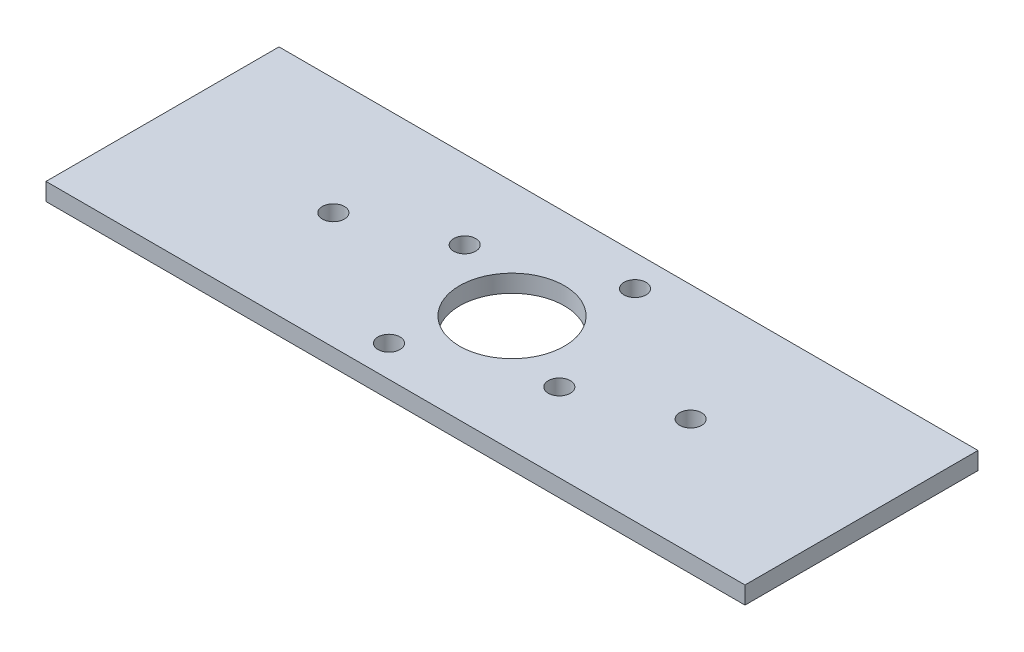
SolidWorks part; units mm, degrees
ref_plane "Front Plane" through (0, 0, 0) normal (0, 0, 1) x (1, 0, 0)
ref_plane "Top Plane" through (0, 0, 0) normal (0, 1, 0) x (1, 0, 0)
ref_plane "Right Plane" through (0, 0, 0) normal (1, 0, 0) x (0, 0, -1)
sketch "Sketch1" plane through (0, 0, 0) normal (0, 1, 0) x (1, 0, 0)
  line L1 (-95.25, -31.75) -> (95.25, -31.75)
  line L2 (-95.25, -31.75) -> (-95.25, 31.75)
  line L3 (-95.25, 31.75) -> (95.25, 31.75)
  line L4 (95.25, -31.75) -> (95.25, 31.75)
  line L5 (-95.25, -31.75) -> (95.25, 31.75) construction
  line L6 (-95.25, 31.75) -> (95.25, -31.75) construction
  point P0 (0, 0)
  dimension "D1" = 190.5
  dimension "D2" = 63.5
extrude "Boss-Extrude1" add sketch "Sketch1" along normal blind 4.7625
sketch "Sketch2" plane through (0, 4.7625, 0) normal (0, 1, 0) x (1, 0, 0)
  line L0 (-31.75, -31.75) -> (-31.75, 31.75)
  line L1 (-95.25, -31.75) -> (95.25, -31.75) construction
  line L2 (95.25, 31.75) -> (-95.25, 31.75) construction
  line L3 (-95.25, 31.75) -> (-95.25, -31.75) construction
  line L4 (31.75, 31.75) -> (31.75, -31.75)
  line L5 (95.25, -31.75) -> (95.25, 31.75) construction
  dimension "D1" = 63.5
  dimension "D2" = 63.5
sketch "Sketch3" plane through (0, 4.7625, 0) normal (0, 1, 0) x (1, 0, 0)
  circle A0 centre (0, 0) radius 14.2875
  dimension "D1" = 28.575
extrude "Cut-Extrude1" cut sketch "Sketch3" against normal through all
hole_wizard "Ø6.0 (6) Diameter Hole1" positions "Sketch4" profile "Sketch5" hole size "Ø6.0" standard "ANSI Metric" end condition through all
sketch "Sketch4" plane through (0, 4.7625, 0) normal (0, 1, 0) x (1, 0, 0)
  line L0 (-31.75, -31.75) -> (-31.75, 31.75) construction
  line L1 (31.75, 31.75) -> (31.75, -31.75) construction
  point P0 (-23.2098, 10.3182)
  point P5 (-10.3182, -23.2098)
  point P7 (10.3182, 23.2098)
  point P9 (23.2098, -10.3182)
  point P22 (-48.6833, 0)
  point P24 (48.6833, 0)
  dimension "D1" = 33.528
  dimension "D2" = 33.528
  dimension "D3" = 33.528
  dimension "D4" = 33.528
  dimension "D5" = 50.8
  dimension "D6" = 50.8
  dimension "D7" = 25.4
  dimension "D8" = 25.4
  dimension "D9" = 16.9333
  dimension "D10" = 16.9333
sketch "Sketch5" plane through (-23.2098, 4.7625, -10.3182) normal (1, 0, 0) x (0, 0, 1)
  line L0 (0, 0) -> (0, 4.7625)
  line L1 (0, 4.7625) -> (3, 4.7625)
  line L2 (3, 4.7625) -> (3, 0)
  line L5 (3, 0) -> (0, 0)
  line L11 (0, -6.35) -> (0, 107.95) construction
  dimension "Thru Hole Dia." = 6
  dimension "Thru Hole Depth" = 4.7625
sketch "Sketch6" plane through (0, 0, 31.75) normal (0, 0, 1) x (1, 0, 0)
  line L0 (-31.75, 4.7625) -> (-31.75, 0)
  line L1 (-95.25, 0) -> (95.25, 0) construction
sketch "Sketch7" plane through (0, 0, 0) normal (0, -1, 0) x (1, 0, 0)
  line L0 (-31.75, 31.75) -> (-31.75, -31.75)
  line L1 (95.25, -31.75) -> (-95.25, -31.75) construction
sketch "Sketch8" plane through (0, 0, 31.75) normal (0, 0, 1) x (1, 0, 0)
  line L0 (31.75, 4.7625) -> (31.75, 0)
  line L1 (-95.25, 0) -> (95.25, 0) construction
sketch "Sketch9" plane through (0, 0, 0) normal (0, -1, 0) x (1, 0, 0)
  line L0 (31.75, 31.75) -> (31.75, -31.75)
  line L1 (95.25, -31.75) -> (-95.25, -31.75) construction
